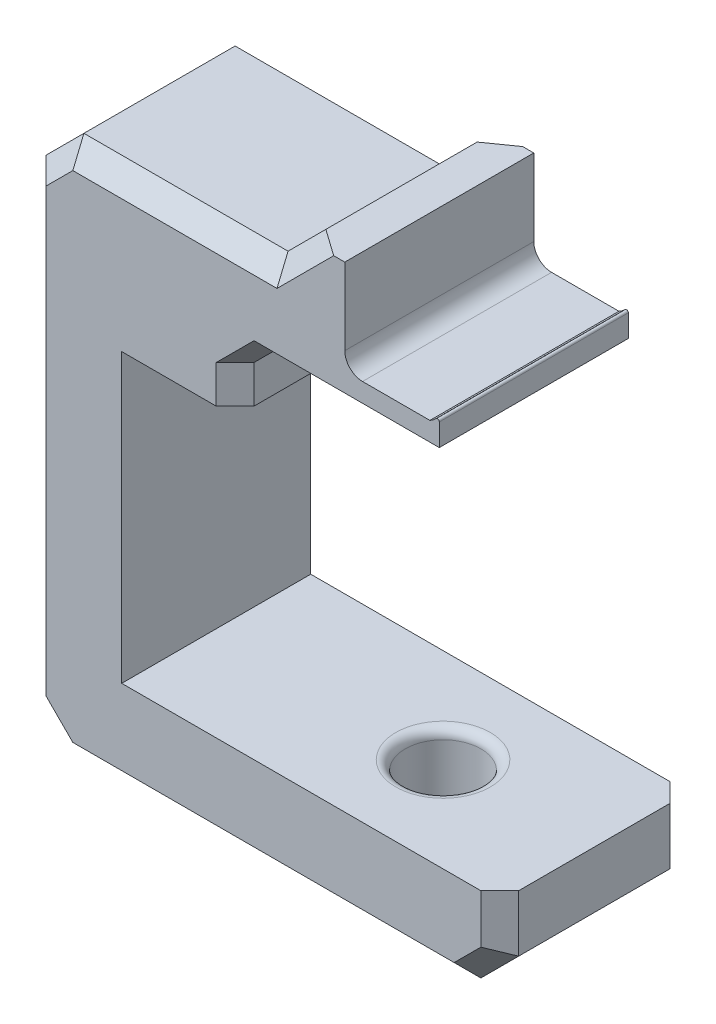
SolidWorks part; units mm, degrees
ref_plane "Plano frontal" through (0, 0, 0) normal (0, 0, 1) x (1, 0, 0)
ref_plane "Plano superior" through (0, 0, 0) normal (0, 1, 0) x (1, 0, 0)
ref_plane "Plano direito" through (0, 0, 0) normal (1, 0, 0) x (0, 0, -1)
sketch "Esboço1" plane through (0, 0, 0) normal (0, 0, 1) x (1, 0, 0)
  line L0 (11, 14.25) -> (0.2, 14.25)
  line L1 (0.2, 11.25) -> (-5.8, 11.25)
  line L3 (-5.8, -3.95) -> (14.2, -3.95)
  line L4 (14.2, -3.95) -> (14.2, -8.95)
  line L5 (14.2, -8.95) -> (-10.8, -8.95)
  line L6 (-10.8, -8.95) -> (-10.8, 19.25)
  line L7 (0.2, 14.25) -> (0.2, 11.25)
  line L9 (-5.8, 11.25) -> (-5.8, -3.95)
  line L10 (11, 14.25) -> (11, 16.25)
  line L11 (10.5044, 16.25) -> (6, 16.25)
  line L12 (6, 16.25) -> (6, 19.25)
  line L13 (6, 19.25) -> (-10.8, 19.25)
  line L14 (11, 16.25) -> (11, 16.4263)
  arc A0 (11, 16.4263) -> (10.8262, 16.4939) centre (10.9, 16.4263) ccw
  arc A1 (10.5044, 16.25) -> (10.8262, 16.4939) centre (10, 17.25) ccw
  dimension "D12" = 0.1
  dimension "D2" = 20
  dimension "D3" = 15.2
  dimension "D4" = 6
  dimension "D5" = 3
  dimension "D6" = 5
  dimension "D7" = 2
  dimension "D8" = 5
  dimension "D10" = 16.8
  dimension "D11" = 5
  dimension "D13" = 0.1763
  dimension "D14" = 0.4956
extrude "Ressalto-extrusão1" add sketch "Esboço1" along normal blind 10
sketch "Esboço3" plane through (0, -8.95, 0) normal (0, -1, 0) x (1, 0, 0)
  line L0 (14.2, 5) -> (6.2, 5) construction
  line L1 (14.2, 10) -> (14.2, 0) construction
  circle A0 centre (6.2, 5) radius 2
  dimension "D1" = 4
  dimension "D2" = 8
extrude "Corte-extrusão1" cut sketch "Esboço3" against normal blind 15
chamfer "Chanfro1" distance 1.6 angle 45 1 edges at (6.2, -8.95, 3)
fillet "Filete1" radius 0.5 1 edges at (6.2, -3.95, 3)
fillet "Filete2" radius 0.94 1 edges at (6, 16.25, 5)
sketch "Esboço5" plane through (0, 0, 10) normal (0, 0, 1) x (1, 0, 0)
  line L0 (6, 19.25) -> (6, 21.25)
  line L1 (6, 21.25) -> (4, 21.25)
  line L2 (4, 21.25) -> (2, 19.25)
  line L3 (6, 19.25) -> (-10.8, 19.25) construction
  line L4 (2, 19.25) -> (6, 19.25)
  dimension "D1" = 135
  dimension "D2" = 2
  dimension "D3" = 2
extrude "Ressalto-extrusão3" add sketch "Esboço5" against normal up to surface (10 mm away) up to face at (3.8473, 9.744, 0)
chamfer "Chanfro5" distance 2 angle 45 3 edges at (14.2, -8.95, 5) (-10.8, -8.95, 5) (-10.8, 19.25, 5)
chamfer "Chanfro4" distance 1 angle 45 22 edges at (5.6, 14.25, 0) (5.6, 14.25, 10) (11, 14.25, 5) (3, 20.25, 0) (3, 20.25, 10) (-3.4, 19.25, 0) (-9.8, 18.25, 0) (-10.8, 5.15, 0) (-9.8, -7.95, 0) (1.7, -8.95, 0) (13.2, -7.95, 0) (14.2, -5.45, 0) (-3.4, 19.25, 10) (-9.8, 18.25, 10) (-10.8, 5.15, 10) (-9.8, -7.95, 10) (1.7, -8.95, 10) (13.2, -7.95, 10) (14.2, -5.45, 10) (0.2, 12.75, 0) (0.2, 12.75, 10) (0.2, 14.25, 5)
